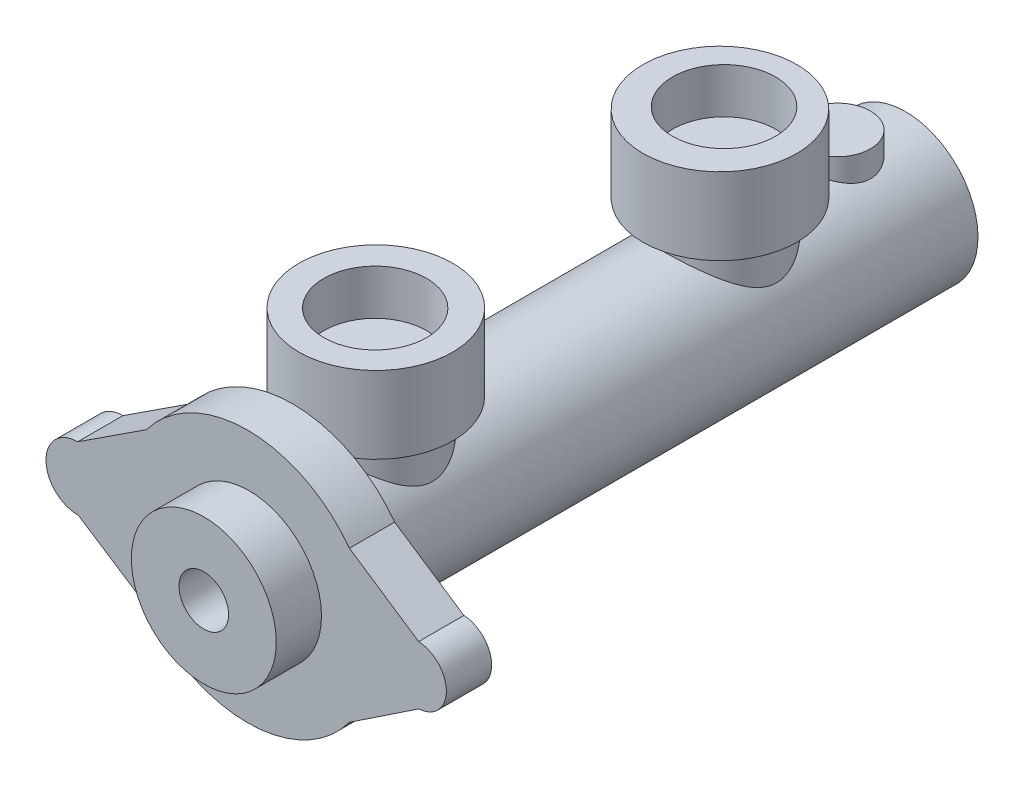
SolidWorks part; units mm, degrees
ref_plane "Ebene vorne" through (0, 0, 0) normal (0, 0, 1) x (1, 0, 0)
ref_plane "Ebene oben" through (0, 0, 0) normal (0, 1, 0) x (1, 0, 0)
ref_plane "Ebene rechts" through (0, 0, 0) normal (1, 0, 0) x (0, 0, -1)
sketch "Skizze1" plane through (0, 0, 0) normal (0, 0, 1) x (1, 0, 0)
  circle A0 centre (0, 0) radius 16
  dimension "D1" = 32
extrude "Aufsatz-Linear austragen1" add sketch "Skizze1" along normal blind 135
sketch "Skizze2" plane through (0, 0, 0) normal (0, 1, 0) x (1, 0, 0)
  circle A0 centre (0, -15) radius 7.25
  dimension "D2" = 14.5
  dimension "D1" = 15
extrude "Aufsatz-Linear austragen2" add sketch "Skizze2" along normal blind 20 contours A0
sketch "Skizze4" plane through (0, 0, 0) normal (0, 1, 0) x (1, 0, 0)
  line L1 (-16, -135) -> (16, -135) construction
  circle A0 centre (0, -41) radius 12.5
  circle A1 centre (0, -117) radius 12.5
  dimension "D2" = 25
  dimension "D3" = 25
  dimension "D1" = 76
  dimension "D4" = 18
extrude "Aufsatz-Linear austragen3" add sketch "Skizze4" along normal blind 20
sketch "Skizze7" plane through (0, 0, 135) normal (0, 0, 1) x (1, 0, 0)
  line L0 (-37.8512, -0.5777) -> (37.1488, -0.5777) construction
  line L5 (-37.8512, 6.4223) -> (-22.6784, 16.319)
  line L6 (-37.6944, -7.576) -> (-22.831, -17.2708)
  line L7 (22.1506, -17.2411) -> (37.5, -7)
  line L8 (22.167, 16.0635) -> (37.4466, 5.8473)
  arc A7 (-37.8512, 6.4223) -> (-37.6944, -7.576) centre (-37.8512, -0.5777) ccw
  arc A8 (37.5, -7) -> (37.4466, 5.8473) centre (37.1488, -0.5777) ccw
  circle A9 centre (-0.3512, -0.5777) radius 28
  circle A10 centre (-0.3512, -0.5777) radius 20
  point P2 (0, 0)
  dimension "D1" = 7
  dimension "D3" = 56
  dimension "D4" = 40
  dimension "D2" = 75
  dimension "D5" = 26.35
  dimension "D7" = 26.35
  dimension "D8" = 26.35
extrude "Aufsatz-Linear austragen4" add sketch "Skizze7" along normal blind 10 separate body
sketch "Skizze8" plane through (0, 20, 0) normal (0, 1, 0) x (1, 0, 0)
  circle A0 centre (0, -41) radius 17
  circle A1 centre (0, -117) radius 17
  dimension "D1" = 34
  dimension "D2" = 34
extrude "Aufsatz-Linear austragen5" add sketch "Skizze8" along normal blind 17
sketch "Skizze9" plane through (0, 37, 0) normal (0, 1, 0) x (1, 0, 0)
  circle A0 centre (0, -40.0872) radius 11.3766
  circle A1 centre (0, -117.1404) radius 11.3549
extrude "Schnitt-Linear austragen2" cut sketch "Skizze9" against normal blind 10
sketch "Skizze10" plane through (0, 0, 135) normal (0, 0, 1) x (1, 0, 0)
  circle A0 centre (0, 0) radius 16
extrude "Aufsatz-Linear austragen6" add sketch "Skizze10" along normal blind 20
sketch "Skizze11" plane through (0, 0, 155) normal (0, 0, 1) x (1, 0, 0)
  circle A0 centre (0, 0) radius 5.4794
extrude "Schnitt-Linear austragen3" cut sketch "Skizze11" against normal blind 20
